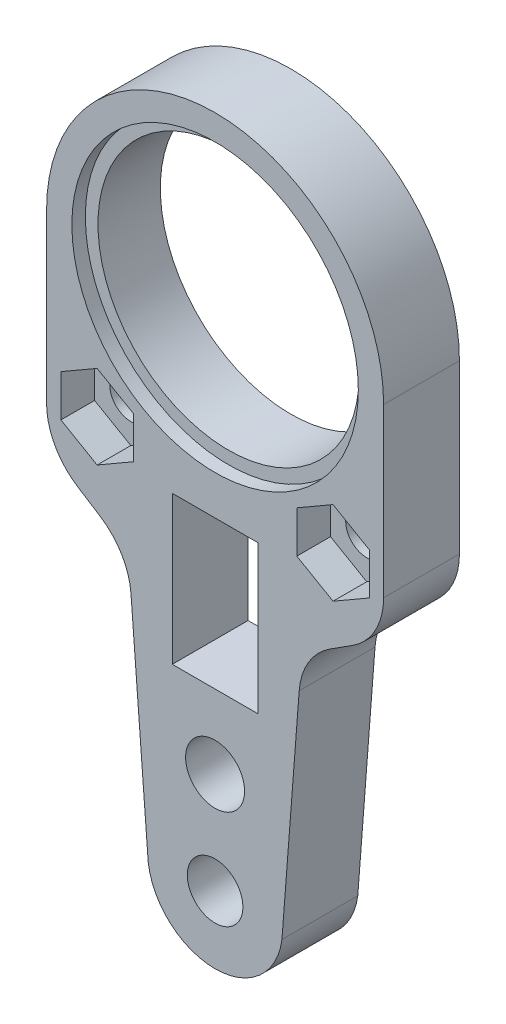
SolidWorks part; units mm, degrees
ref_plane "Front Plane" through (0, 0, 0) normal (0, 0, 1) x (1, 0, 0)
ref_plane "Top Plane" through (0, 0, 0) normal (0, 1, 0) x (1, 0, 0)
ref_plane "Right Plane" through (0, 0, 0) normal (1, 0, 0) x (0, 0, -1)
sketch "草图1" plane through (0, 0, 0) normal (0, 0, 1) x (1, 0, 0)
  line L2 (-10, 0) -> (-10, -12.1238)
  line L3 (-10, -12.1238) -> (-3.9672, -30.5111) construction
  line L4 (10, 0) -> (10, -12.1238)
  line L5 (10, -12.1238) -> (3.9672, -30.5111) construction
  line L7 (-10, -12.1238) -> (-5.1442, -15.2247)
  line L8 (-5.1442, -15.2247) -> (-3.9672, -30.5111)
  line L9 (3.9672, -30.5111) -> (5.1442, -15.2247)
  line L10 (5.1442, -15.2247) -> (10, -12.1238)
  line L13 (-2.5407, -10.8297) -> (2.5407, -10.8297)
  line L14 (-2.5407, -10.8297) -> (-2.5407, -19.6197)
  line L15 (-2.5407, -19.6197) -> (2.5407, -19.6197)
  line L16 (2.5407, -10.8297) -> (2.5407, -19.6197)
  line L17 (-2.5407, -10.8297) -> (2.5407, -19.6197) construction
  line L18 (-2.5407, -19.6197) -> (2.5407, -10.8297) construction
  circle A0 centre (0, 0) radius 7.75
  arc A1 (10, 0) -> (-10, 0) centre (0, 0) ccw
  arc A2 (3.9672, -30.5111) -> (-3.9672, -30.5111) centre (0, -30) cw
  circle A3 centre (0, 0) radius 11.5 construction
  circle A4 centre (-7, -9.1241) radius 1.25
  circle A5 centre (7, -9.1241) radius 1.25
  circle A6 centre (0, -30) radius 1.65
  circle A7 centre (0, 0) radius 1.65
  circle A8 centre (0, 0) radius 1.65
  circle A9 centre (0, -24) radius 1.75
  point P21 (5.1442, -15.2247)
  point P37 (0, -15.2247)
  dimension "D1" = 15.5
  dimension "D2" = 10
  dimension "D3" = 2.5
  dimension "D4" = 2.5
  dimension "D5" = 23
  dimension "D7" = 3.3
  dimension "D8" = 3.5
  dimension "D9" = 4
  dimension "D6" = 14
  dimension "D10" = 24
  dimension "D11" = 30
extrude "凸台-拉伸1" add sketch "草图1" along normal blind 4.5
sketch "草图2" plane through (0, 0, 4.5) normal (0, 0, 1) x (1, 0, 0)
  circle A0 centre (0, 0) radius 8.5
  dimension "D1" = 17
extrude "切除-拉伸1" cut sketch "草图2" against normal blind 0.8
fillet "圆角1" radius 4 4 edges at (-5.1442, -15.2247, 2.25) (5.1442, -15.2247, 2.25) (10, -12.1238, 2.25) (-10, -12.1238, 2.25)
sketch "草图3" plane through (0, 0, 4.5) normal (0, 0, 1) x (1, 0, 0)
  line L0 (7, -6.6415) -> (9.15, -7.8828)
  line L1 (9.15, -7.8828) -> (9.15, -10.3654)
  line L2 (9.15, -10.3654) -> (7, -11.6067)
  line L3 (7, -11.6067) -> (4.85, -10.3654)
  line L4 (4.85, -10.3654) -> (4.85, -7.8828)
  line L5 (4.85, -7.8828) -> (7, -6.6415)
  line L6 (7, -6.6415) -> (7, -11.6067) construction
  line L7 (4.85, -7.8828) -> (9.15, -10.3654) construction
  line L8 (-7, -6.6415) -> (-4.85, -7.8828)
  line L9 (-4.85, -7.8828) -> (-4.85, -10.3654)
  line L10 (-4.85, -10.3654) -> (-7, -11.6067)
  line L11 (-7, -11.6067) -> (-9.15, -10.3654)
  line L12 (-9.15, -10.3654) -> (-9.15, -7.8828)
  line L13 (-9.15, -7.8828) -> (-7, -6.6415)
  line L14 (-7, -6.6415) -> (-7, -11.6067) construction
  line L15 (-9.15, -7.8828) -> (-4.85, -10.3654) construction
  circle A0 centre (7, -9.1241) radius 1.25 construction
  point P2 (-7, -9.1241)
  point P7 (7, -9.1241)
  point P14 (-7, -9.1241)
  dimension "D1" = 120
  dimension "D2" = 240
  dimension "D3" = 4.3
  dimension "D4" = 120
  dimension "D5" = 240
  dimension "D6" = 4.3
extrude "切除-拉伸2" cut sketch "草图3" against normal blind 2
